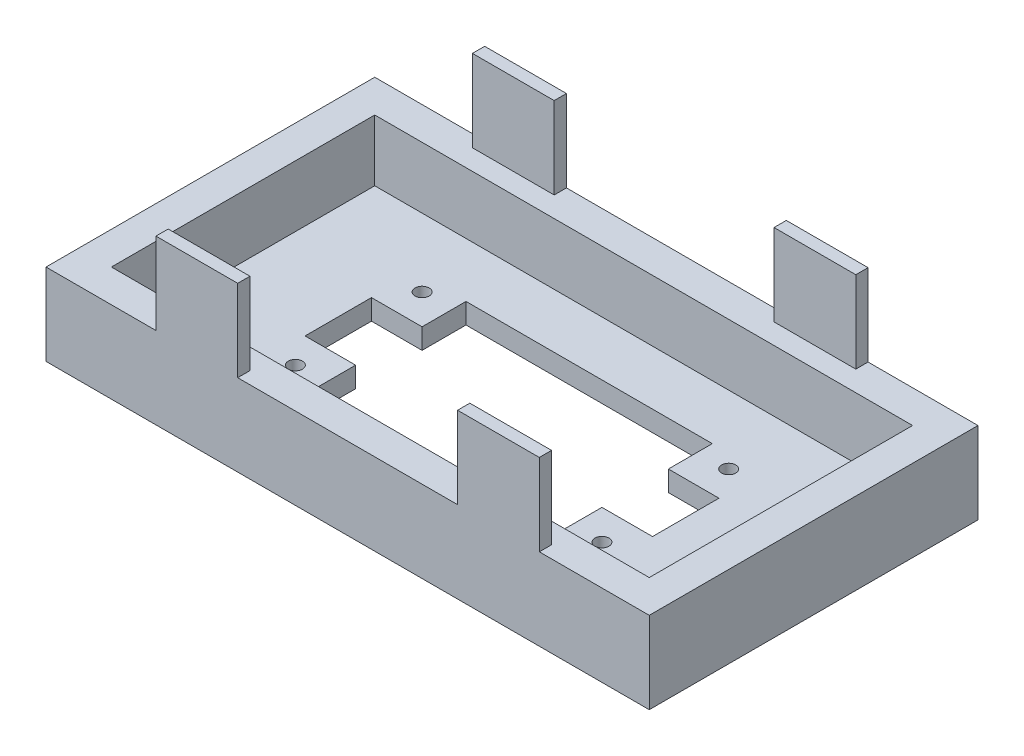
SolidWorks part; units mm, degrees
ref_plane "Front Plane" through (0, 0, 0) normal (0, 0, 1) x (1, 0, 0)
ref_plane "Top Plane" through (0, 0, 0) normal (0, 1, 0) x (1, 0, 0)
ref_plane "Right Plane" through (0, 0, 0) normal (1, 0, 0) x (0, 0, -1)
sketch "Sketch1" plane through (0, 0, 0) normal (0, 1, 0) x (1, 0, 0)
  line L1 (0, 0) -> (147.57, 0)
  line L2 (0, 0) -> (0, 80.42)
  line L3 (0, 80.42) -> (147.57, 80.42)
  line L4 (147.57, 0) -> (147.57, 80.42)
  line L5 (0, 0) -> (147.57, 80.42) construction
  line L6 (0, 80.42) -> (147.57, 0) construction
  point P4 (73.785, 40.21)
  dimension "D1" = 80.42
  dimension "D2" = 147.57
extrude "Boss-Extrude1" add sketch "Sketch1" along normal blind 20
sketch "Sketch2" plane through (0, 20, 0) normal (0, 1, 0) x (1, 0, 0)
  line L0 (0, 80.42) -> (0, 0) construction
  line L1 (8, 72.42) -> (139.57, 72.42)
  line L2 (8, 72.42) -> (8, 8)
  line L3 (8, 8) -> (139.57, 8)
  line L4 (139.57, 72.42) -> (139.57, 8)
  line L5 (8, 72.42) -> (139.57, 8) construction
  line L6 (8, 8) -> (139.57, 72.42) construction
  line L7 (147.57, 0) -> (147.57, 80.42) construction
  line L8 (147.57, 80.42) -> (0, 80.42) construction
  line L9 (0, 0) -> (147.57, 0) construction
  point P4 (73.785, 40.21)
  dimension "D1" = 8
  dimension "D2" = 8
  dimension "D3" = 8
  dimension "D4" = 8
extrude "Cut-Extrude1" cut sketch "Sketch2" against normal blind 15
sketch "Sketch3" plane through (0, 0, 0) normal (0, -1, 0) x (1, 0, 0)
  line L0 (147.57, 0) -> (147.57, -80.42) construction
  line L1 (36.285, -24.71) -> (111.285, -24.71) construction
  line L2 (36.285, -24.71) -> (36.285, -55.71) construction
  line L3 (36.285, -55.71) -> (111.285, -55.71) construction
  line L4 (111.285, -24.71) -> (111.285, -55.71) construction
  line L5 (36.285, -24.71) -> (111.285, -55.71) construction
  line L6 (36.285, -55.71) -> (111.285, -24.71) construction
  line L7 (0, 0) -> (147.57, 0) construction
  point P4 (73.785, -40.21)
  dimension "D1" = 75
  dimension "D2" = 31
  dimension "D3" = 73.785
  dimension "D4" = 40.21
hole_wizard "CBORE for #4 Binding Head Machine Screw1" positions "3DSketch1" profile "Sketch4" counterbore size "#4" standard "ANSI Inch" end condition through all
sketch3d "3DSketch1"
  point P0 (36.285, 0, -24.71)
  point P3 (36.285, 0, -55.71)
  point P6 (111.285, 0, -24.71)
  point P9 (111.285, 0, -55.71)
sketch "Sketch4" plane through (36.285, 0, -24.71) normal (1, 0, 0) x (0, 0, -1)
  line L0 (0, 0) -> (0, 20)
  line L1 (0, 20) -> (1.7272, 20)
  line L3 (1.7272, 20) -> (1.7272, 1.7272)
  line L4 (1.7272, 1.7272) -> (3.3731, 1.7272)
  line L5 (3.3731, 1.7272) -> (3.3731, 0)
  line L7 (3.3731, 0) -> (0, 0)
  line L11 (0, -6.35) -> (0, 107.95) construction
  dimension "Thru Hole Dia." = 3.4544
  dimension "Thru Hole Depth" = 20
  dimension "C'Bore Dia." = 6.7462
  dimension "C'Bore Depth" = 1.7272
sketch "Sketch5" plane through (0, 0, 0) normal (0, -1, 0) x (1, 0, 0)
  line L1 (36.285, -24.71) -> (36.285, -55.71) construction
  line L3 (111.285, -24.71) -> (111.285, -55.71) construction
  line L6 (103.9119, -32.0831) -> (103.9119, -21.3369)
  line L7 (103.9119, -21.3369) -> (43.6581, -21.3369)
  line L8 (43.6581, -21.3369) -> (43.6581, -32.0831)
  line L10 (36.285, -24.71) -> (111.285, -24.71) construction
  line L11 (43.6581, -32.0831) -> (31.285, -32.0831)
  line L12 (31.285, -32.0831) -> (31.285, -48.3369)
  line L14 (116.285, -48.3369) -> (116.285, -32.0831)
  line L15 (103.9119, -32.0831) -> (116.285, -32.0831)
  line L16 (31.285, -48.3369) -> (43.6581, -48.3369)
  line L17 (43.6581, -48.3369) -> (43.6581, -59.0831)
  line L18 (43.6581, -59.0831) -> (103.9119, -59.0831)
  line L19 (103.9119, -59.0831) -> (103.9119, -48.3369)
  line L20 (103.9119, -48.3369) -> (116.285, -48.3369)
  line L21 (36.285, -55.71) -> (111.285, -55.71) construction
  circle A0 centre (36.285, -55.71) radius 3.3731 construction
  circle A1 centre (111.285, -55.71) radius 3.3731 construction
  circle A2 centre (111.285, -24.71) radius 3.3731 construction
  circle A3 centre (111.285, -24.71) radius 3.3731 construction
  circle A4 centre (36.285, -24.71) radius 3.3731 construction
  circle A5 centre (36.285, -24.71) radius 3.3731 construction
  circle A6 centre (36.285, -55.71) radius 3.3731 construction
  circle A7 centre (111.285, -55.71) radius 3.3731 construction
  point P0 (36.285, -21.3369)
  point P4 (36.285, -52.3369)
  point P8 (33.285, -26.2521)
  point P13 (111.285, -52.3369)
  point P16 (111.285, -28.0831)
  point P19 (107.9119, -24.71)
  point P22 (36.285, -28.0831)
  point P27 (39.6581, -24.71)
  point P34 (114.285, -23.1679)
  point P39 (36.285, -59.0831)
  point P40 (39.6581, -55.71)
  point P43 (107.9119, -55.71)
  dimension "D1" = 5
  dimension "D2" = 4
  dimension "D3" = 0
  dimension "D4" = 4
  dimension "D5" = 4
  dimension "D6" = 4
  dimension "D7" = 0
  dimension "D8" = 2
  dimension "D9" = 2
  dimension "D10" = 5
  dimension "D11" = 3.3731
  dimension "D12" = 4
  dimension "D13" = 4
  dimension "D14" = 4
  dimension "D15" = 4
extrude "Cut-Extrude2" cut sketch "Sketch5" against normal through all
sketch "Sketch6" plane through (0, 20, 0) normal (0, 1, 0) x (1, 0, 0)
  line L0 (147.57, 80.42) -> (0, 80.42) construction
  line L1 (26.8925, 80.42) -> (46.8925, 80.42)
  line L2 (26.8925, 80.42) -> (26.8925, 77.42)
  line L3 (26.8925, 77.42) -> (46.8925, 77.42)
  line L4 (46.8925, 80.42) -> (46.8925, 77.42)
  line L5 (26.8925, 80.42) -> (46.8925, 77.42) construction
  line L6 (26.8925, 77.42) -> (46.8925, 80.42) construction
  line L7 (0, 80.42) -> (0, 0) construction
  point P4 (36.8925, 78.92)
  dimension "D1" = 3
  dimension "D2" = 20
  dimension "D3" = 36.8925
extrude "Boss-Extrude2" add sketch "Sketch6" along normal blind 20
sketch "Sketch7" plane through (0, 20, 0) normal (0, 1, 0) x (1, 0, 0)
  line L0 (73.785, 40.21) -> (73.785, 80.42) construction
  line L1 (147.57, 80.42) -> (46.8925, 80.42) construction
  line L2 (73.785, 80.42) -> (73.785, 0) construction
  line L3 (0, 0) -> (147.57, 0) construction
  line L4 (0, 40.21) -> (147.57, 40.21) construction
  line L5 (0, 80.42) -> (0, 0) construction
  line L6 (147.57, 0) -> (147.57, 80.42) construction
ref_plane "Plane1" through (0, 0, -40.21) normal (0, 0, -1) x (1, 0, 0)
ref_plane "Plane2" through (73.785, 0, 0) normal (1, 0, 0) x (0, 0, 1)
mirror "Mirror1" about plane through (73.785, 0, 0) normal (1, 0, 0) of "Boss-Extrude2"
mirror "Mirror2" about plane through (0, 0, -40.21) normal (0, 0, -1) of "Mirror1", "Boss-Extrude2"
sketch "Sketch8" plane through (0, 0, 0) normal (0, 0, 1) x (1, 0, 0)
  line L0 (36.8925, 40) -> (36.8925, 30) construction
  line L1 (46.8925, 40) -> (26.8925, 40) construction
  dimension "D1" = 10
hole_wizard "#4 (0.209) Diameter Hole1" positions "3DSketch2" profile "Sketch9" hole size "#4" standard "ANSI Inch"
sketch3d "3DSketch2"
  point P0 (36.8925, 30, 0)
sketch "Sketch9" plane through (36.8925, 30, 0) normal (1, 0, 0) x (0, -1, 0)
  line L0 (0, 0) -> (0, 80.42)
  line L1 (0, 80.42) -> (2.6543, 80.42)
  line L2 (2.6543, 80.42) -> (2.6543, 0)
  line L5 (2.6543, 0) -> (0, 0)
  line L11 (0, -6.35) -> (0, 107.95) construction
  dimension "Thru Hole Dia." = 5.3086
  dimension "Thru Hole Depth" = 80.42
sketch "Sketch10" plane through (0, 0, 0) normal (0, 0, 1) x (1, 0, 0)
  line L0 (110.6775, 40) -> (110.6775, 30) construction
  line L1 (100.6775, 40) -> (120.6775, 40) construction
  dimension "D1" = 10
hole_wizard "#4 (0.209) Diameter Hole2" positions "3DSketch3" profile "Sketch11" hole size "#4" standard "ANSI Inch"
sketch3d "3DSketch3"
  point P0 (110.6775, 30, 0)
sketch "Sketch11" plane through (110.6775, 30, 0) normal (1, 0, 0) x (0, -1, 0)
  line L0 (0, 0) -> (0, 80.42)
  line L1 (0, 80.42) -> (2.6543, 80.42)
  line L2 (2.6543, 80.42) -> (2.6543, 0)
  line L5 (2.6543, 0) -> (0, 0)
  line L11 (0, -6.35) -> (0, 107.95) construction
  dimension "Thru Hole Dia." = 5.3086
  dimension "Thru Hole Depth" = 80.42
